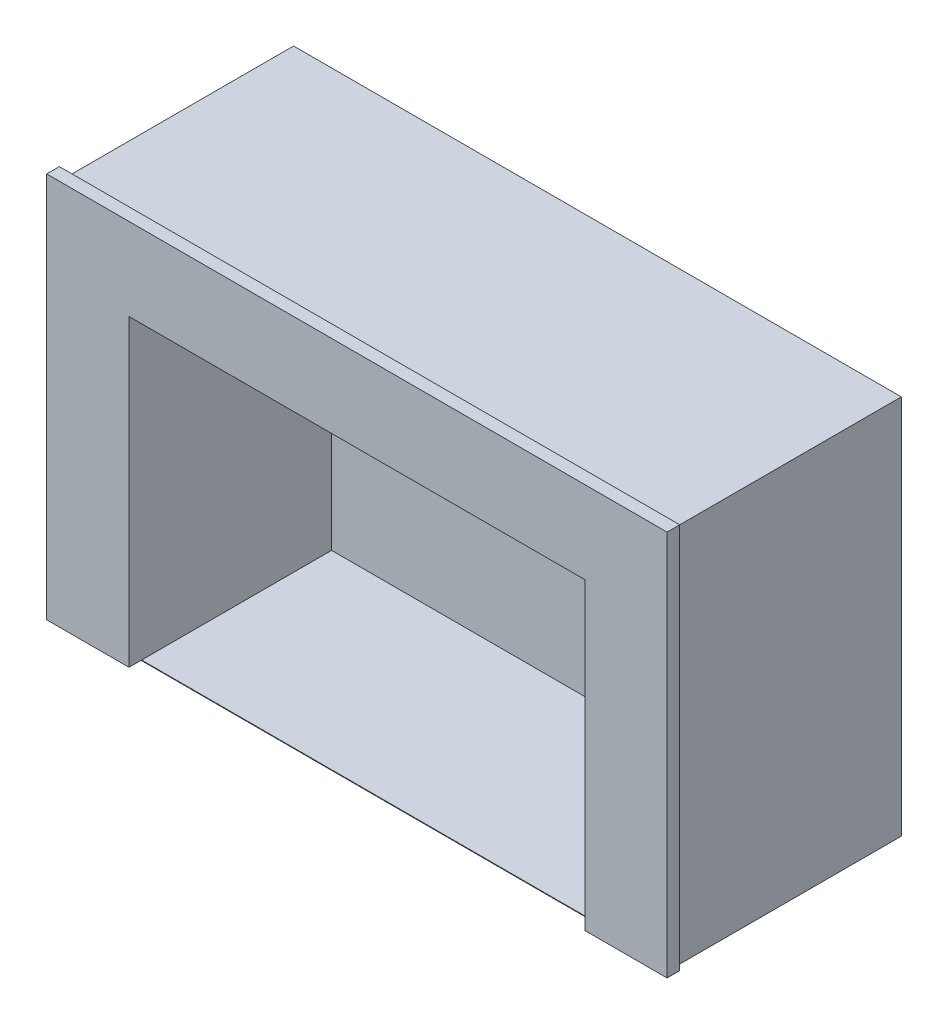
SolidWorks part; units mm, degrees
ref_plane "Front Plane" through (0, 0, 0) normal (0, 0, 1) x (1, 0, 0)
ref_plane "Top Plane" through (0, 0, 0) normal (0, 1, 0) x (1, 0, 0)
ref_plane "Right Plane" through (0, 0, 0) normal (1, 0, 0) x (0, 0, -1)
sketch "Sketch1" plane through (0, 0, 0) normal (0, 0, 1) x (1, 0, 0)
  line L0 (-1219.2, 0) -> (-914.4, 0)
  line L1 (-914.4, 0) -> (-914.4, 1219.2)
  line L2 (-914.4, 1219.2) -> (914.4, 1219.2)
  line L3 (914.4, 1219.2) -> (914.4, 0)
  line L4 (914.4, 0) -> (1219.2, 0)
  line L5 (1219.2, 0) -> (1219.2, 1524)
  line L6 (1219.2, 1524) -> (-1219.2, 1524)
  line L7 (-1219.2, 1524) -> (-1219.2, 0)
  point P3 (0, 0)
  dimension "D1" = 1828.8
  dimension "D2" = 1524
  dimension "D3" = 1219.2
  dimension "D4" = 304.8
  dimension "D5" = 914.4
extrude "Boss-Extrude1" add sketch "Sketch1" against normal blind 762
sketch "Sketch2" plane through (0, 0, -762) normal (0, 0, -1) x (-1, 0, 0)
  line L1 (-1219.2, 1524) -> (1219.2, 1524)
  line L2 (-1219.2, 1524) -> (-1219.2, 0)
  line L3 (-1219.2, 0) -> (1219.2, 0)
  line L4 (1219.2, 1524) -> (1219.2, 0)
extrude "Boss-Extrude2" add sketch "Sketch2" along normal blind 152.4
sketch "Sketch3" plane through (0, 0, 0) normal (0, -1, 0) x (1, 0, 0)
  line L1 (1219.2, -914.4) -> (-1219.2, -914.4)
  line L2 (1219.2, -914.4) -> (1219.2, 0)
  line L3 (1219.2, 0) -> (-1219.2, 0)
  line L4 (-1219.2, -914.4) -> (-1219.2, 0)
extrude "Boss-Extrude3" add sketch "Sketch3" along normal blind 2.54
sketch "Sketch4" plane through (0, 0, 0) normal (0, 0, 1) x (1, 0, 0)
  line L0 (-914.4, 0) -> (-1244.6, 0)
  line L4 (-914.4, 1219.2) -> (914.4, 1219.2)
  line L5 (914.4, 1219.2) -> (914.4, 0)
  line L6 (914.4, 0) -> (1244.6, 0)
  line L7 (-914.4, 1219.2) -> (-914.4, 0)
  line L8 (-1244.6, -27.94) -> (1244.6, -27.94)
  line L9 (1244.6, -27.94) -> (1244.6, 1549.4)
  line L10 (1244.6, 1549.4) -> (-1244.6, 1549.4)
  line L11 (-1244.6, 1549.4) -> (-1244.6, -27.94)
  line L13 (1244.6, 0) -> (1244.6, 1549.4)
  line L14 (1244.6, 1549.4) -> (-1244.6, 1549.4)
  line L15 (-1244.6, 1549.4) -> (-1244.6, 0)
  dimension "D1" = 25.4
extrude "Boss-Extrude4" add sketch "Sketch4" along normal blind 50.8
